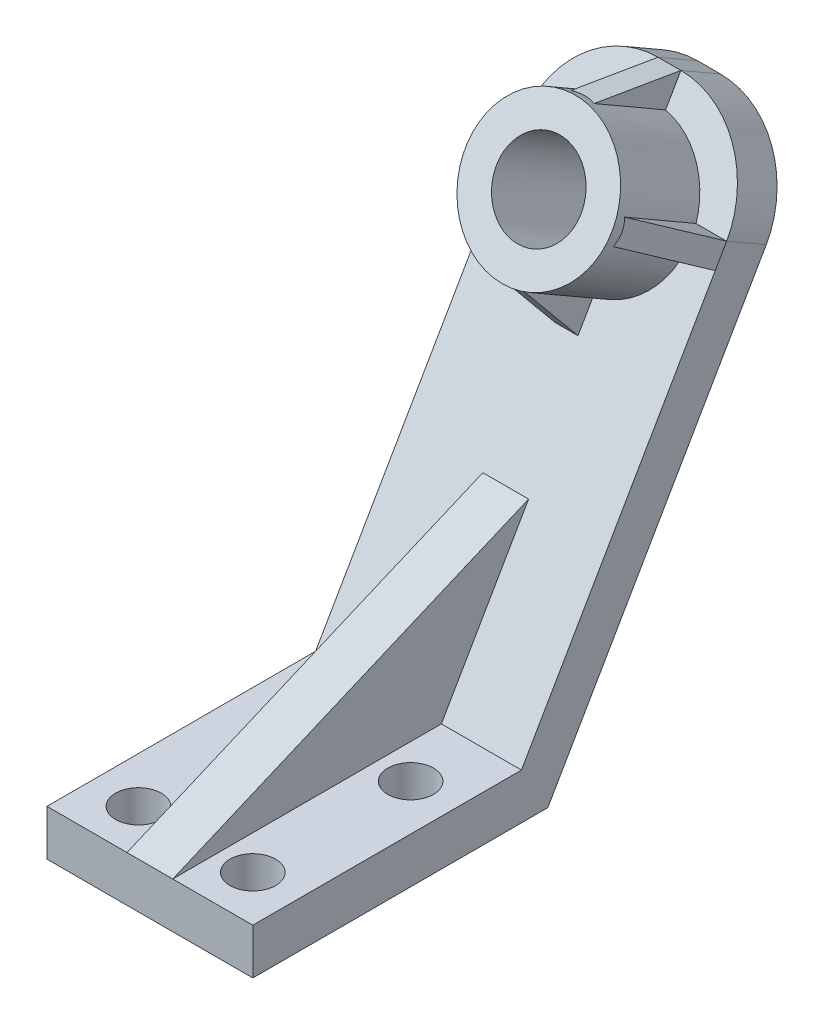
SolidWorks part; units mm, degrees
ref_plane "Front Plane" through (0, 0, 0) normal (0, 0, 1) x (1, 0, 0)
ref_plane "Top Plane" through (0, 0, 0) normal (0, 1, 0) x (1, 0, 0)
ref_plane "Right Plane" through (0, 0, 0) normal (1, 0, 0) x (0, 0, -1)
sketch "Sketch1" plane through (0, 0, 0) normal (1, 0, 0) x (0, 0, -1)
  line L0 (0, 0) -> (129, 0)
  line L1 (129, 0) -> (244.5, 200.0519)
  line L2 (0, 0) -> (0, 20)
  line L3 (244.5, 200.0519) -> (227.1795, 210.0519)
  line L4 (227.1795, 210.0519) -> (117.453, 20)
  line L5 (117.453, 20) -> (0, 20)
  dimension "D1" = 129
  dimension "D2" = 231
  dimension "D3" = 120
  dimension "D4" = 20
  dimension "D5" = 20
extrude "Boss-Extrude1" add sketch "Sketch1" along normal mid plane 90
sketch "Sketch2" plane through (0, 0, 0) normal (1, 0, 0) x (0, 0, -1)
  line L0 (0, 20) -> (155.5814, 86.0404)
  line L1 (227.1795, 210.0519) -> (117.453, 20) construction
  line L2 (0, 20) -> (117.453, 20) construction
  dimension "D1" = 23
rib "Rib1" sketch "Sketch2" sketch "Sketch2" thickness 20 extrusion direction parallel to sketch draft on no parameters "D1"=20
sketch "Sketch3" plane through (0, 20, 0) normal (0, 1, 0) x (1, 0, 0)
  line L0 (-10, 117.453) -> (-10, 0) construction
  line L1 (-10, 117.453) -> (-45, 117.453) construction
  line L2 (0, 0) -> (0, 120.1666) construction
  line L4 (10, 0) -> (-10, 0) construction
  circle A0 centre (-25, 20) radius 10
  circle A1 centre (-25, 89) radius 10
  circle A2 centre (25, 20) radius 10
  circle A3 centre (25, 89) radius 10
  point P17 (0, 0)
  dimension "D1" = 20
  dimension "D4" = 69
  dimension "D2" = 20
  dimension "D3" = 20
extrude "Cut-Extrude1" cut sketch "Sketch3" against normal through all
ref_plane "Plane1" through (0, -45.8586, -79.4295) normal (0, 0.5, 0.866) x (1, 0, 0)
fillet "Fillet1" radius 40 2 edges at (45, 205.0519, -235.8397) (-45, 205.0519, -235.8397)
sketch "Sketch5" plane through (0, -45.8586, -79.4295) normal (0, 0.5, 0.866) x (1, 0, 0)
  line L0 (0, 295.5) -> (0, 250.5) construction
  line L1 (5, 295.5) -> (-5, 295.5) construction
  line L2 (10, 17.3205) -> (-10, 17.3205) construction
  line L3 (-10, 152.3039) -> (10, 152.3039) construction
  circle A0 centre (0, 250.5) radius 32
  point P8 (0, 17.3205)
  point P11 (0, 152.3039)
  dimension "D2" = 64
  dimension "D1" = 45
extrude "Boss-Extrude2" add sketch "Sketch5" along normal blind 40
sketch "Sketch6" plane through (0, -25.8586, -44.7885) normal (0, 0.5, 0.866) x (1, 0, 0)
  circle A0 centre (0, 250.5) radius 18.5
  dimension "D1" = 37
extrude "Cut-Extrude2" cut sketch "Sketch6" against normal through all
sketch "Sketch7" plane through (0, 0, 0) normal (1, 0, 0) x (0, 0, -1)
  line L1 (220.6795, 198.7935) -> (186.0385, 218.7935) construction
  line L2 (190.3686, 216.2935) -> (227.1795, 210.0519)
  dimension "D1" = 5
rib "Rib2" sketch "Sketch7" sketch "Sketch7" thickness 10 extrusion direction parallel to sketch draft on no parameters "D1"=10
pattern_circular "CirPattern1" count 4 over 360 about axis through (0, 216.9394, -125.25) along (0, 0.5, 0.866) of "Rib2"
